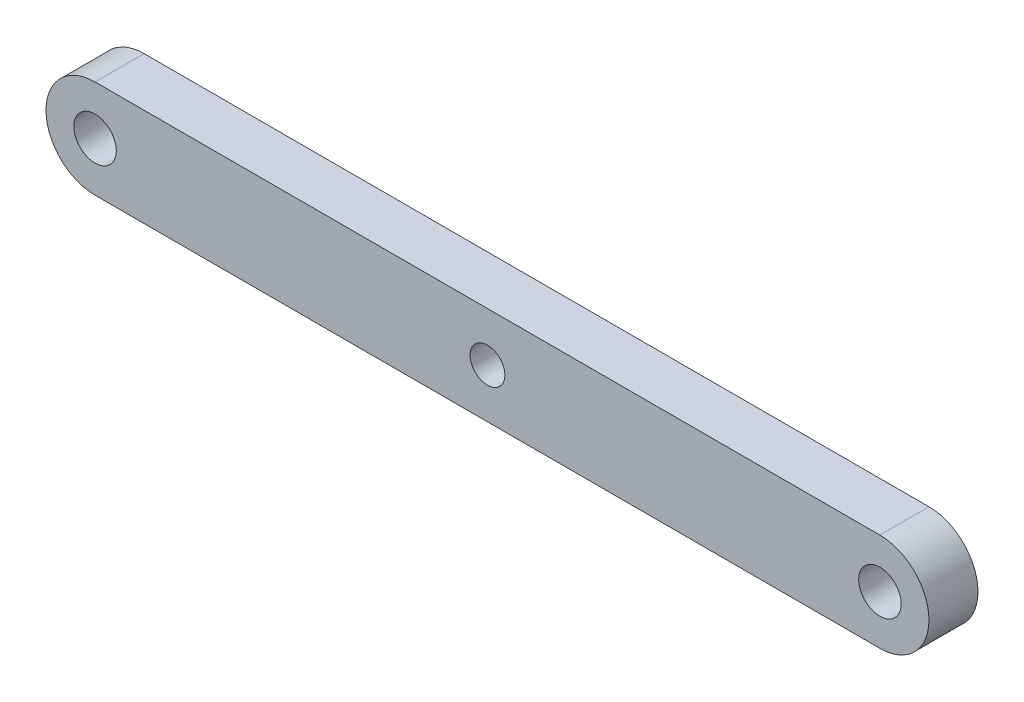
SolidWorks part; units mm, degrees
ref_plane "Front Plane" through (0, 0, 0) normal (0, 0, 1) x (1, 0, 0)
ref_plane "Top Plane" through (0, 0, 0) normal (0, 1, 0) x (1, 0, 0)
ref_plane "Right Plane" through (0, 0, 0) normal (1, 0, 0) x (0, 0, -1)
sketch "Sketch1" plane through (0, 0, 0) normal (0, 0, 1) x (1, 0, 0)
  line L0 (0, 0) -> (101.6, 0) construction
  line L1 (0, 6.35) -> (101.6, 6.35)
  line L2 (0, -6.35) -> (101.6, -6.35)
  arc A0 (0, 6.35) -> (0, -6.35) centre (0, 0) ccw
  arc A1 (101.6, -6.35) -> (101.6, 6.35) centre (101.6, 0) ccw
  circle A2 centre (101.6, 0) radius 2.575 construction
  circle A3 centre (50.8, 0) radius 2.0625 construction
  point P3 (50.8, 0)
  dimension "D2" = 6.35
  dimension "D3" = 5.15
  dimension "D4" = 4.125
  dimension "D1" = 101.6
extrude "Boss-Extrude1" add sketch "Sketch1" along normal blind 6.35
sketch "Sketch2" plane through (0, 0, 6.35) normal (0, 0, 1) x (1, 0, 0)
  line L0 (0, 0) -> (101.6, 0) construction
  line L1 (-1.3843, 0.4953) -> (1.3843, 0.4953)
  line L2 (-1.3843, 0.4953) -> (-1.3843, -0.4953)
  line L3 (-1.3843, -0.4953) -> (1.3843, -0.4953)
  line L4 (1.3843, 0.4953) -> (1.3843, -0.4953)
  line L5 (0, -0.4953) -> (0, 0.4953) construction
  line L6 (-1.3843, 0) -> (1.3843, 0) construction
  point P88 (0, 0)
  dimension "D1" = 0.9906
  dimension "D2" = 2.7686
extrude "Cut-Extrude1" [suppressed] cut sketch "Sketch2" against normal blind 6.35
hole_wizard "M5 Clearance Hole1" positions "Sketch3" profile "Sketch4" hole size "M5" standard "ANSI Metric" end condition through all
sketch "Sketch3" plane through (0, 0, 0) normal (0, 0, -1) x (-1, 0, 0)
  point P0 (-101.6, 0)
sketch "Sketch4" plane through (101.6, 0, 0) normal (1, 0, 0) x (0, 1, 0)
  line L0 (0, 0) -> (0, 6.35)
  line L1 (0, 6.35) -> (2.75, 6.35)
  line L2 (2.75, 6.35) -> (2.75, 0)
  line L5 (2.75, 0) -> (0, 0)
  line L11 (0, -6.35) -> (0, 107.95) construction
  dimension "Thru Hole Dia." = 5.5
  dimension "Thru Hole Depth" = 6.35
hole_wizard "M4 Clearance Hole1" positions "Sketch5" profile "Sketch6" hole size "M4" standard "ANSI Metric" end condition through all
sketch "Sketch5" plane through (0, 0, 0) normal (0, 0, -1) x (-1, 0, 0)
  point P0 (-50.8, 0)
sketch "Sketch6" plane through (50.8, 0, 0) normal (1, 0, 0) x (0, 1, 0)
  line L0 (0, 0) -> (0, 6.35)
  line L1 (0, 6.35) -> (2.25, 6.35)
  line L2 (2.25, 6.35) -> (2.25, 0)
  line L5 (2.25, 0) -> (0, 0)
  line L11 (0, -6.35) -> (0, 107.95) construction
  dimension "Thru Hole Dia." = 4.5
  dimension "Thru Hole Depth" = 6.35
hole_wizard "M5 Clearance Hole2" positions "Sketch7" profile "Sketch8" hole size "M5" standard "ANSI Metric" end condition through all
sketch "Sketch7" plane through (0, 0, 6.35) normal (0, 0, 1) x (1, 0, 0)
  point P0 (0, 0)
sketch "Sketch8" plane through (0, 0, 6.35) normal (1, 0, 0) x (0, -1, 0)
  line L0 (0, 0) -> (0, 6.35)
  line L1 (0, 6.35) -> (2.75, 6.35)
  line L2 (2.75, 6.35) -> (2.75, 0)
  line L5 (2.75, 0) -> (0, 0)
  line L11 (0, -6.35) -> (0, 107.95) construction
  dimension "Thru Hole Dia." = 5.5
  dimension "Thru Hole Depth" = 6.35
equation "\"spring width\"= .099in"
equation "\"spring thick\"= .029in"
equation "\"stock thick\"= .25in"
equation "\"D1@Boss-Extrude1\"=\"stock thick\""
equation "\"D1@Sketch2\"=\"spring thick\" + .01"
equation "\"D2@Sketch2\"=\"spring width\" + .01"
equation "\"D1@Cut-Extrude1\"=\"stock thick\""
